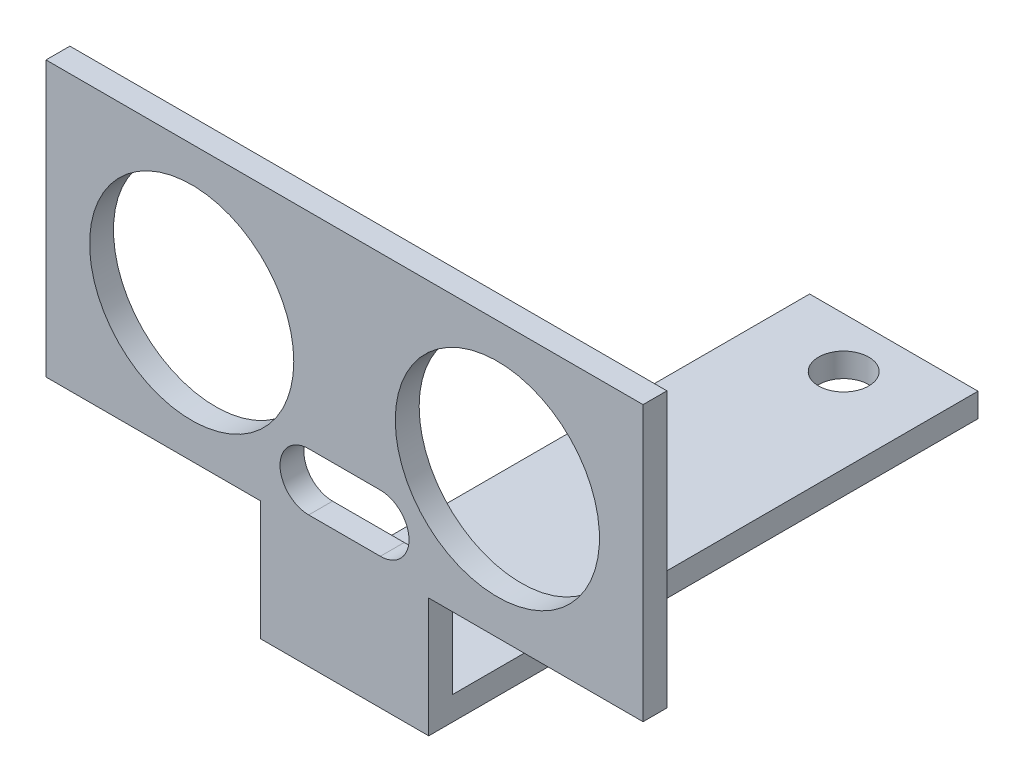
SolidWorks part; units mm, degrees
ref_plane "Plano frontal" through (0, 0, 0) normal (0, 0, 1) x (1, 0, 0)
ref_plane "Plano superior" through (0, 0, 0) normal (0, 1, 0) x (1, 0, 0)
ref_plane "Plano direito" through (0, 0, 0) normal (1, 0, 0) x (0, 0, -1)
sketch "baseEsb" plane through (0, 0, 0) normal (0, 1, 0) x (1, 0, 0)
  line L1 (0, 0) -> (14.1, 0)
  line L2 (0, 0) -> (0, 46)
  line L3 (0, 46) -> (14.1, 46)
  line L4 (14.1, 0) -> (14.1, 46)
  dimension "D1" = 46
  dimension "D2" = 14.1
extrude "base" add sketch "baseEsb" along normal blind 2
sketch "furosFixEsb" plane through (0, 2, 0) normal (0, 1, 0) x (1, 0, 0)
  line L0 (7.05, 0) -> (7.05, 46) construction
  line L1 (0, 0) -> (14.1, 0) construction
  line L2 (14.1, 46) -> (0, 46) construction
  circle A0 centre (7.05, 10.1) radius 2.1
  circle A1 centre (7.05, 41.8) radius 2.1
  dimension "D3" = 4.2
  dimension "D4" = 4.2
  dimension "D1" = 31.7
  dimension "D2" = 4.2
extrude "furosFix" cut sketch "furosFixEsb" against normal blind 2
sketch "holderEsb" plane through (0, 0, 0) normal (0, 0, 1) x (1, 0, 0)
  line L0 (14.1, 2) -> (14.1, 0) construction
  line L1 (0, 0) -> (14.1, 0)
  line L2 (0, 0) -> (0, 10)
  line L4 (14.1, 0) -> (14.1, 10)
  line L5 (7.05, 0) -> (7.05, 33) construction
  line L7 (-17.95, 10) -> (-17.95, 33)
  line L8 (-17.95, 33) -> (32.05, 33)
  line L9 (32.05, 10) -> (32.05, 33)
  line L10 (-17.95, 10) -> (0, 10)
  line L11 (32.05, 10) -> (14.1, 10)
  dimension "D1" = 23
  dimension "D2" = 50
  dimension "D3" = 10
extrude "holder" add sketch "holderEsb" against normal blind 2
sketch "furosUSesb" plane through (0, 0, 0) normal (0, 0, 1) x (1, 0, 0)
  line L0 (7.05, 0) -> (7.05, 33) construction
  line L1 (0, 0) -> (14.1, 0) construction
  line L2 (32.05, 33) -> (-17.95, 33) construction
  line L3 (0, 10) -> (14.1, 10) construction
  line L4 (-17.95, 33) -> (-17.95, 10) construction
  line L9 (4.05, 13.4) -> (10.05, 13.4) construction
  line L10 (4.05, 15.8) -> (10.05, 15.8)
  line L11 (4.05, 11) -> (10.05, 11)
  circle A0 centre (-5.75, 21.5) radius 8.55
  circle A2 centre (19.85, 21.5) radius 8.55
  arc A3 (4.05, 15.8) -> (4.05, 11) centre (4.05, 13.4) ccw
  arc A4 (10.05, 11) -> (10.05, 15.8) centre (10.05, 13.4) ccw
  point P20 (-17.95, 21.5)
  point P24 (7.05, 13.4)
  point P29 (7.05, 11)
  dimension "D1" = 17.1
  dimension "D2" = 1
  dimension "D4" = 4.8
  dimension "D3" = 12.8
  dimension "D5" = 6
extrude "furosUS" cut sketch "furosUSesb" against normal blind 2
